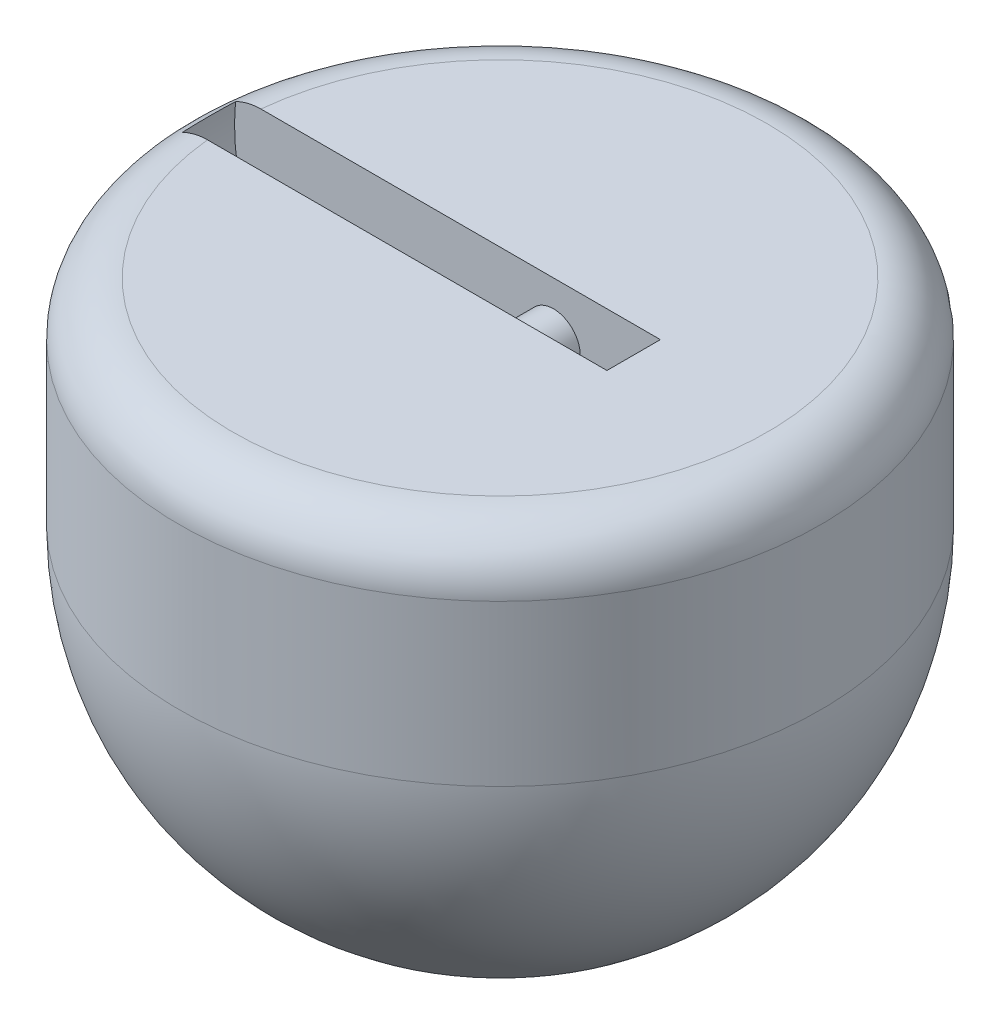
SolidWorks part; units mm, degrees
ref_plane "前视基准面" through (0, 0, 0) normal (0, 0, 1) x (1, 0, 0)
ref_plane "上视基准面" through (0, 0, 0) normal (0, 1, 0) x (1, 0, 0)
ref_plane "右视基准面" through (0, 0, 0) normal (1, 0, 0) x (0, 0, -1)
other "Configuration Table"
sketch "草图1" plane through (0, 0, 0) normal (0, 0, 1) x (1, 0, 0)
  line L0 (0, -13.959) -> (0, 11.1604) construction
  line L1 (0, 6.041) -> (10, 6.041)
  line L2 (12, 4.041) -> (12, -1.959)
  line L3 (0, -13.959) -> (0, 6.041)
  arc A0 (12, -1.959) -> (0, -13.959) centre (0, -1.959) cw
  arc A1 (10, 6.041) -> (12, 4.041) centre (10, 4.041) cw
  point P9 (12, 6.041)
  dimension "D3" = 2
  dimension "D1" = 12
  dimension "D2" = 8
  dimension "D4" = 20
revolve "旋转1" add sketch "草图1" angle 360 about L0
sketch "草图2" plane through (0, 0, 0) normal (0, 0, 1) x (1, 0, 0)
  line L0 (0, -14.6207) -> (0, 11.1515) construction
  line L2 (10, 6.041) -> (-10, 6.041) construction
  line L3 (5, 6.041) -> (-10, 6.041)
  arc A0 (5, 6.041) -> (-10.8985, 5.8278) centre (-2.9373, 5.041) cw
  arc A3 (-10, 6.041) -> (-12, 4.041) centre (-10, 4.041) ccw construction
  arc A4 (-10, 6.041) -> (-10.8985, 5.8278) centre (-10, 4.041) ccw
  point P7 (0, 0)
  dimension "D1" = 1
  dimension "D3" = 8
  dimension "D2" = 5
extrude "切除-拉伸2" cut sketch "草图2" against normal mid plane 2
sketch "草图3" plane through (0, 0, -1) normal (0, 0, 1) x (1, 0, 0)
  line L0 (5, 6.041) -> (-9.9499, 6.041) construction
  line L1 (0, 0) -> (0, 15.4121) construction
  circle A0 centre (-3, 1.041) radius 1
  circle A1 centre (1, 4.041) radius 1
  dimension "D1" = 2
  dimension "D2" = 2
  dimension "D3" = 3
  dimension "D4" = 4
  dimension "D5" = 2
  dimension "D6" = 1
extrude "凸台-拉伸2" add sketch "草图3" along normal blind 2
